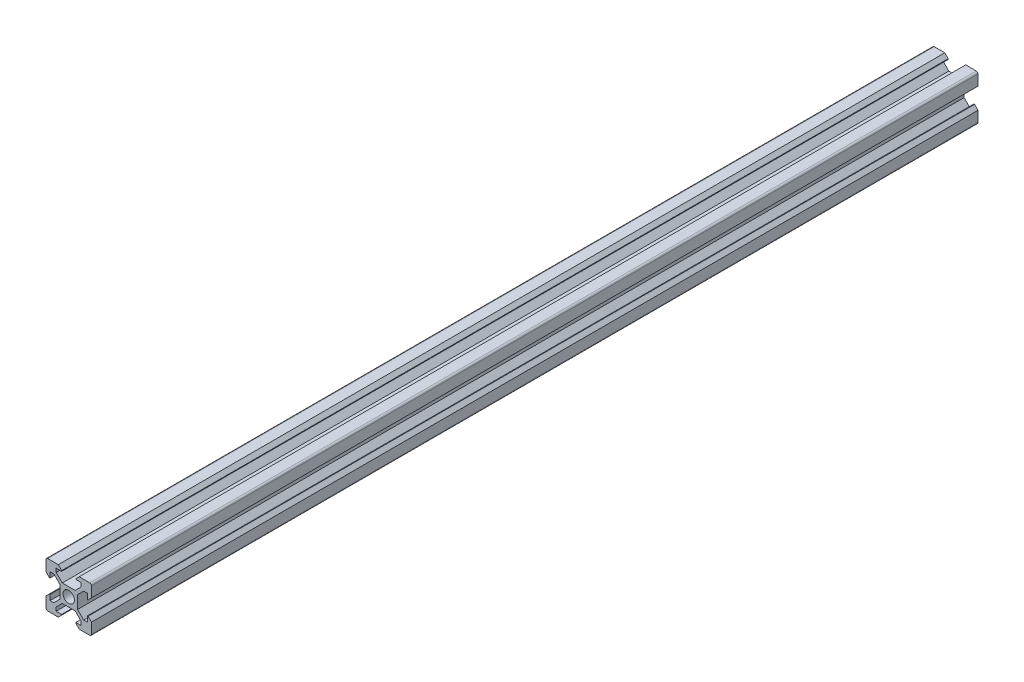
SolidWorks part; units mm, degrees
other "Markup1"
sketch "Sketch1" plane through (10, 10, 480) normal (0.5774, 0.5773, 0.5774) x (0.7071, 0, -0.7071)
ref_plane "Alzado" through (0, 0, 0) normal (0, 0, 1) x (1, 0, 0)
ref_plane "Planta" through (0, 0, 0) normal (0, 1, 0) x (1, 0, 0)
ref_plane "Vista lateral" through (0, 0, 0) normal (1, 0, 0) x (0, 0, -1)
sketch "Croquis1" plane through (0, 0, 0) normal (0, 0, 1) x (1, 0, 0)
  line L0 (-4.6, 10) -> (-3.1, 8.5)
  line L3 (-4.6, 10) -> (-9.25, 10)
  line L5 (-3.1, 8.5) -> (-3.1, 8.2)
  line L6 (-3.1, 8.2) -> (-5.5, 8.2)
  line L7 (-5.5, 8.2) -> (-5.5, 6.5607)
  line L8 (-5.5, 6.5607) -> (-2.84, 3.9007)
  line L9 (-2.84, 3.9007) -> (0, 3.9007)
  line L10 (0, 0) -> (-15.3499, 15.3499) construction
  line L11 (-3.9007, 2.84) -> (-3.9007, 0)
  line L12 (-6.5607, 5.5) -> (-3.9007, 2.84)
  line L13 (-8.2, 5.5) -> (-6.5607, 5.5)
  line L14 (-8.2, 3.1) -> (-8.2, 5.5)
  line L15 (-8.5, 3.1) -> (-8.2, 3.1)
  line L16 (-10, 4.6) -> (-10, 9.25)
  line L17 (-10, 4.6) -> (-8.5, 3.1)
  line L18 (10, 4.6) -> (8.5, 3.1)
  line L19 (10, 4.6) -> (10, 9.25)
  line L20 (8.5, 3.1) -> (8.2, 3.1)
  line L21 (8.2, 3.1) -> (8.2, 5.5)
  line L22 (8.2, 5.5) -> (6.5607, 5.5)
  line L23 (6.5607, 5.5) -> (3.9007, 2.84)
  line L24 (3.9007, 2.84) -> (3.9007, 0)
  line L25 (5.5, 6.5607) -> (2.84, 3.9007)
  line L26 (5.5, 8.2) -> (5.5, 6.5607)
  line L27 (3.1, 8.2) -> (5.5, 8.2)
  line L28 (3.1, 8.5) -> (3.1, 8.2)
  line L29 (4.6, 10) -> (9.25, 10)
  line L30 (4.6, 10) -> (3.1, 8.5)
  line L31 (2.84, 3.9007) -> (0, 3.9007)
  line L32 (4.6, -10) -> (3.1, -8.5)
  line L33 (4.6, -10) -> (9.25, -10)
  line L34 (3.1, -8.5) -> (3.1, -8.2)
  line L35 (3.1, -8.2) -> (5.5, -8.2)
  line L36 (5.5, -8.2) -> (5.5, -6.5607)
  line L37 (5.5, -6.5607) -> (2.84, -3.9007)
  line L38 (2.84, -3.9007) -> (0, -3.9007)
  line L39 (6.5607, -5.5) -> (3.9007, -2.84)
  line L40 (8.2, -5.5) -> (6.5607, -5.5)
  line L41 (8.2, -3.1) -> (8.2, -5.5)
  line L42 (8.5, -3.1) -> (8.2, -3.1)
  line L43 (10, -4.6) -> (10, -9.25)
  line L44 (10, -4.6) -> (8.5, -3.1)
  line L45 (3.9007, -2.84) -> (3.9007, 0)
  line L46 (-10, -4.6) -> (-8.5, -3.1)
  line L47 (-10, -4.6) -> (-10, -9.25)
  line L48 (-8.5, -3.1) -> (-8.2, -3.1)
  line L49 (-8.2, -3.1) -> (-8.2, -5.5)
  line L50 (-8.2, -5.5) -> (-6.5607, -5.5)
  line L51 (-6.5607, -5.5) -> (-3.9007, -2.84)
  line L52 (-3.9007, -2.84) -> (-3.9007, 0)
  line L53 (-5.5, -6.5607) -> (-2.84, -3.9007)
  line L54 (-5.5, -8.2) -> (-5.5, -6.5607)
  line L55 (-3.1, -8.2) -> (-5.5, -8.2)
  line L56 (-3.1, -8.5) -> (-3.1, -8.2)
  line L57 (-4.6, -10) -> (-9.25, -10)
  line L58 (-4.6, -10) -> (-3.1, -8.5)
  line L59 (-2.84, -3.9007) -> (0, -3.9007)
  circle A0 centre (0, 0) radius 2.5
  arc A1 (-9.25, 10) -> (-10, 9.25) centre (-9.25, 9.25) ccw
  arc A2 (10, 9.25) -> (9.25, 10) centre (9.25, 9.25) ccw
  arc A3 (9.25, -10) -> (10, -9.25) centre (9.25, -9.25) ccw
  arc A4 (-10, -9.25) -> (-9.25, -10) centre (-9.25, -9.25) ccw
  point P18 (-10, 10)
  point P37 (10, 10)
  point P55 (10, -10)
  point P73 (-10, -10)
  point P79 (0, 0)
  dimension "D1" = 5
  dimension "D5" = 0.75
  dimension "D2" = 10
  dimension "D3" = 10
  dimension "D4" = 4.6
  dimension "D6" = 5.5
  dimension "D7" = 135
  dimension "D8" = 0.75
  dimension "D9" = 225
  dimension "D10" = 2.84
  dimension "D11" = 1.8
  dimension "D12" = 3.1
  dimension "D13" = 4
extrude "Saliente-Extruir1" add sketch "Croquis1" along normal blind 480
sketch "Sketch2" plane through (0, 0, 0) normal (1, 0, 0) x (0, 0, -1)
  line L0 (-90, 79.4753) -> (-90, -100.6342) construction
  line L1 (90, -21.3385) -> (-90, -21.3385)
  line L2 (90, -21.3385) -> (90, 21.3385)
  line L3 (90, 21.3385) -> (-90, 21.3385)
  line L4 (-90, -21.3385) -> (-90, 21.3385)
  line L5 (90, -21.3385) -> (-90, 21.3385) construction
  line L6 (90, 21.3385) -> (-90, -21.3385) construction
  line L7 (-480, -2.84) -> (-480, 2.84) construction
  point P0 (0, 0)
  dimension "D1" = 390
extrude "Cut-Extrude1" cut sketch "Sketch2" against normal blind 31 and the other way blind 65
